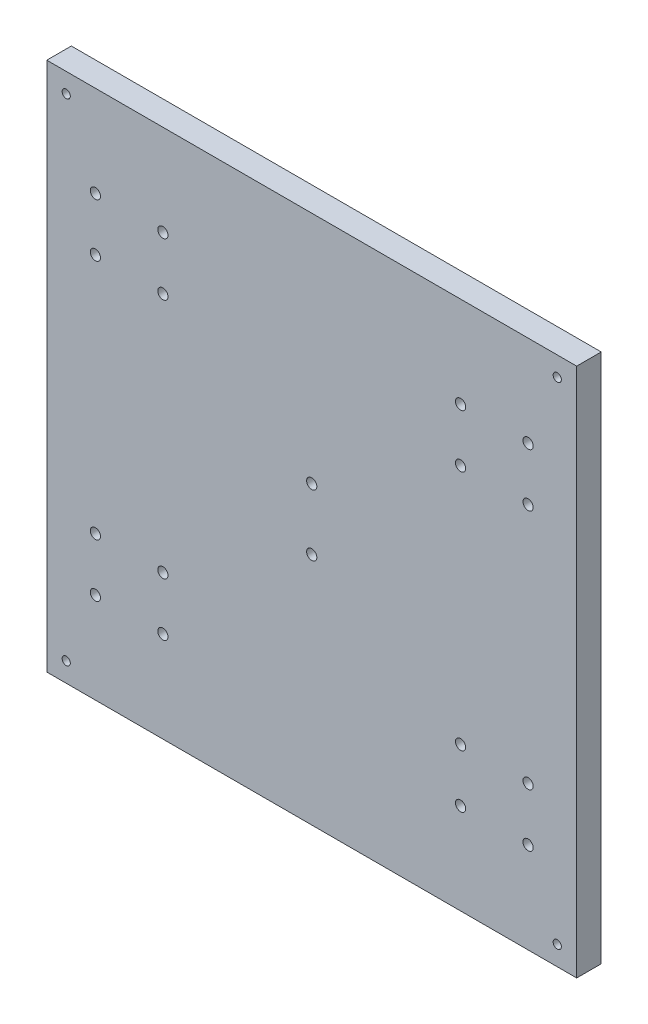
SolidWorks part; units mm, degrees
ref_plane "Ön Düzlem" through (0, 0, 0) normal (0, 0, 1) x (1, 0, 0)
ref_plane "Üst Düzlem" through (0, 0, 0) normal (0, 1, 0) x (1, 0, 0)
ref_plane "Sağ Düzlem" through (0, 0, 0) normal (1, 0, 0) x (0, 0, -1)
sketch "Çizim1" plane through (0, 0, 0) normal (0, 0, 1) x (1, 0, 0)
  line L0 (0, 160) -> (0, -160) construction
  line L1 (-160, -160) -> (160, -160)
  line L2 (-160, -160) -> (-160, 160)
  line L3 (-160, 160) -> (160, 160)
  line L4 (160, -160) -> (160, 160)
  line L5 (-160, -160) -> (160, 160) construction
  line L6 (-160, 160) -> (160, -160) construction
  line L7 (-160, 0) -> (160, 0) construction
  line L8 (-105.75, 85) -> (-72.75, 59) construction
  line L9 (-105.75, 85) -> (-72.75, 85) construction
  circle A0 centre (-105.75, 85) radius 2.5
  circle A1 centre (-72.75, 85) radius 2.5
  circle A2 centre (-105.75, 59) radius 2.5
  circle A3 centre (-72.75, 59) radius 2.5
  circle A4 centre (-120, 120) radius 2
  circle A5 centre (-105.75, -59) radius 2.5
  circle A6 centre (-105.75, -85) radius 2.5
  circle A7 centre (-120, -120) radius 2
  circle A8 centre (-72.75, -59) radius 2.5
  circle A9 centre (-72.75, -85) radius 2.5
  circle A10 centre (72.75, -85) radius 2.5
  circle A11 centre (72.75, -59) radius 2.5
  circle A12 centre (120, -120) radius 2
  circle A13 centre (105.75, -85) radius 2.5
  circle A14 centre (105.75, -59) radius 2.5
  circle A15 centre (120, 120) radius 2
  circle A16 centre (72.75, 59) radius 2.5
  circle A17 centre (105.75, 59) radius 2.5
  circle A18 centre (72.75, 85) radius 2.5
  circle A19 centre (105.75, 85) radius 2.5
  point P0 (0, 0)
  point P50 (-89.25, 85)
  dimension "D5" = 4
  dimension "D6" = 5
  dimension "D8" = 33
  dimension "D4" = 120
  dimension "D10" = 85
  dimension "D1" = 320
  dimension "D2" = 320
  dimension "D3" = 120
  dimension "D7" = 26
  dimension "D9" = 89.25
extrude "Yükseklik-Ekstrüzyon1" add sketch "Çizim1" along normal blind 12
sketch "Sketch2" plane through (0, 0, 12) normal (0, 0, 1) x (1, 0, 0)
  line L1 (-155, -155) -> (155, -155)
  line L2 (-155, -155) -> (-155, 155)
  line L3 (-155, 155) -> (155, 155)
  line L4 (155, -155) -> (155, 155)
  line L5 (-155, -155) -> (155, 155) construction
  line L6 (-155, 155) -> (155, -155) construction
  line L7 (-160, -160) -> (160, -160)
  line L8 (-160, -160) -> (-160, 160)
  line L9 (-160, 160) -> (160, 160)
  line L10 (160, -160) -> (160, 160)
  line L11 (-160, -160) -> (160, 160) construction
  line L12 (-160, 160) -> (160, -160) construction
  point P0 (0, 0)
  point P6 (0, 0)
  dimension "D1" = 310
  dimension "D2" = 310
extrude "Cut-Extrude1" cut sketch "Sketch2" against normal blind 10
sketch "Sketch3" plane through (0, 0, 12) normal (0, 0, 1) x (1, 0, 0)
  line L1 (-129.5, -129.5) -> (129.5, -129.5)
  line L2 (-129.5, -129.5) -> (-129.5, 129.5)
  line L3 (-129.5, 129.5) -> (129.5, 129.5)
  line L4 (129.5, -129.5) -> (129.5, 129.5)
  line L5 (-129.5, -129.5) -> (129.5, 129.5) construction
  line L6 (-129.5, 129.5) -> (129.5, -129.5) construction
  point P0 (0, 0)
  dimension "D1" = 259
  dimension "D2" = 259
extrude "Cut-Extrude2" cut sketch "Sketch3" against normal through all flip side to cut
sketch "Sketch4" plane through (0, 0, 12) normal (0, 0, 1) x (1, 0, 0)
  line L0 (0, 129.5) -> (0, -145.1845) construction
  line L1 (129.5, 129.5) -> (-129.5, 129.5) construction
  line L2 (129.5, 0) -> (-154.0734, 0) construction
  line L3 (129.5, -129.5) -> (129.5, 129.5) construction
  circle A0 centre (0, 15) radius 2.5
  circle A1 centre (0, -15) radius 2.5
  dimension "D1" = 5
  dimension "D2" = 15
  dimension "D3" = 15
extrude "Cut-Extrude3" cut sketch "Sketch4" against normal through all
